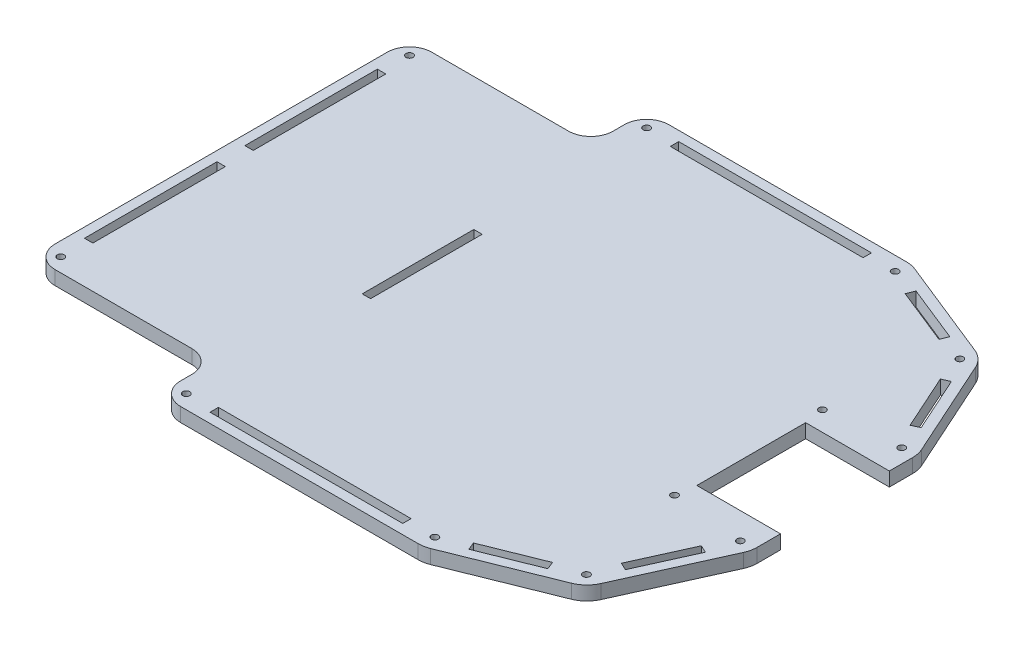
SolidWorks part; units mm, degrees
material "PVC rigido"
ref_plane "Piano frontale" through (0, 0, 0) normal (0, 0, 1) x (1, 0, 0)
ref_plane "Piano superiore" through (0, 0, 0) normal (0, 1, 0) x (1, 0, 0)
ref_plane "Piano destro" through (0, 0, 0) normal (1, 0, 0) x (0, 0, -1)
sketch "Schizzo1" plane through (0, 0, 0) normal (0, 1, 0) x (1, 0, 0)
  line L0 (65, 67.5) -> (65, 87.5)
  line L1 (0, 67.5) -> (65, 67.5)
  line L2 (0, 67.5) -> (0, -67.5)
  line L3 (0, -67.5) -> (65, -67.5)
  line L4 (65, 67.5) -> (65, -67.5) construction
  line L5 (65, 87.5) -> (160.0521, 87.5)
  line L6 (220, 30) -> (220, -30)
  line L7 (160.0521, -87.5) -> (65, -87.5)
  line L8 (65, -87.5) -> (65, -67.5)
  line L9 (220, 0) -> (65, 0) construction
  line L10 (220, 30) -> (201.5852, 70.8013)
  line L11 (201.5852, 70.8013) -> (160.0521, 87.5)
  line L12 (220, -30) -> (201.5852, -70.8013)
  line L13 (201.5852, -70.8013) -> (160.0521, -87.5)
  arc A0 (220, 30) -> (160.0521, 87.5) centre (160.0521, 27.5) ccw construction
  arc A1 (160.0521, -87.5) -> (220, -30) centre (160.0521, -27.5) ccw construction
  dimension "D5" = 60
  dimension "D6" = 60
  dimension "D1" = 135
  dimension "D2" = 65
  dimension "D3" = 155
  dimension "D4" = 20
extrude "Estrusione-Estrusione1" add sketch "Schizzo1" along normal blind 5
hole_wizard "Foro filettato M3x0.5-1" positions "Schizzo9" profile "Schizzo8" tap size "M3x0.5" standard "Ansi Metric"
sketch "Schizzo9" plane through (0, 5, 0) normal (0, 1, 0) x (1, 0, 0)
  line L102 (5, -62.5) -> (70, -62.5)
  line L103 (5, 62.5) -> (5, -62.5)
  line L104 (70, 62.5) -> (5, 62.5)
  line L105 (70, 82.5) -> (70, 62.5)
  line L106 (70, -62.5) -> (70, -82.5)
  line L107 (70, -82.5) -> (159.0846, -82.5)
  line L108 (159.0846, -82.5) -> (197.8549, -66.9121)
  line L109 (197.8549, -66.9121) -> (215, -28.9239)
  line L110 (215, -28.9239) -> (215, 28.9239)
  line L111 (215, 28.9239) -> (197.8549, 66.9121)
  line L112 (197.8549, 66.9121) -> (159.0846, 82.5)
  line L113 (159.0846, 82.5) -> (70, 82.5)
  line L114 (5, -62.5) -> (70, -62.5) construction
  line L115 (5, 62.5) -> (5, -62.5) construction
  line L116 (70, 62.5) -> (5, 62.5) construction
  line L117 (70, 82.5) -> (70, 62.5) construction
  line L118 (70, -62.5) -> (70, -82.5) construction
  line L119 (70, -82.5) -> (159.0846, -82.5) construction
  line L120 (159.0846, -82.5) -> (197.8549, -66.9121) construction
  line L121 (197.8549, -66.9121) -> (215, -28.9239) construction
  line L122 (215, -28.9239) -> (215, 28.9239) construction
  line L123 (215, 28.9239) -> (197.8549, 66.9121) construction
  line L124 (197.8549, 66.9121) -> (159.0846, 82.5) construction
  line L125 (159.0846, 82.5) -> (70, 82.5) construction
  point P0 (197.8549, 66.9121)
  point P2 (215, 28.9239)
  point P4 (215, -28.9239)
  point P6 (197.8549, -66.9121)
  point P8 (159.0846, -82.5)
  point P10 (159.0846, 82.5)
  point P12 (70, 82.5)
  point P14 (70, -82.5)
  point P16 (5, -62.5)
  point P18 (5, 62.5)
  dimension "D1" = 5
sketch "Schizzo8" plane through (197.8549, 5, -66.9121) normal (1, 0, 0) x (0, 0, 1)
  line L0 (0, 0) -> (0, 8.2511)
  line L1 (0, 8.2511) -> (1.25, 7.5)
  line L2 (1.25, 7.5) -> (1.25, 0)
  line L5 (1.25, 0) -> (0, 0)
  line L10 (0, 8.2511) -> (-1.25, 7.5) construction
  line L11 (0, -6.35) -> (0, 107.95) construction
  dimension "Tap Drill Dia." = 2.5
  dimension "Tap Drill Depth" = 7.5
  dimension "Drill Angle" = 118
cosmetic thread "Filettatura del foro1" parameters "D1"=5, "D2"=3
cosmetic thread "Filettatura del foro2" parameters "D1"=5, "D2"=3
cosmetic thread "Filettatura del foro3" parameters "D1"=5, "D2"=3
cosmetic thread "Filettatura del foro4" parameters "D1"=5, "D2"=3
cosmetic thread "Filettatura del foro5" parameters "D1"=5, "D2"=3
cosmetic thread "Filettatura del foro6" parameters "D1"=5, "D2"=3
cosmetic thread "Filettatura del foro7" parameters "D1"=5, "D2"=3
cosmetic thread "Filettatura del foro8" parameters "D1"=5, "D2"=3
cosmetic thread "Filettatura del foro9" parameters "D1"=5, "D2"=3
cosmetic thread "Filettatura del foro10" parameters "D1"=5, "D2"=3
sketch "Schizzo4" plane through (0, 5, 0) normal (0, 1, 0) x (1, 0, 0)
  line L0 (112.5261, -87.5) -> (112.5261, -84) construction
  line L1 (80, -84) -> (149.0846, -84)
  line L2 (80, -84) -> (80, -81)
  line L3 (80, -81) -> (149.0846, -81)
  line L4 (149.0846, -84) -> (149.0846, -81)
  line L5 (209.5191, 37.4216) -> (200.6014, 57.1804)
  line L6 (149.0846, -82.5) -> (159.0846, -82.5) construction
  line L7 (159.0846, -82.5) -> (168.3628, -78.7696) construction
  line L8 (168.3628, -78.7696) -> (188.5767, -70.6425) construction
  line L9 (80, 84) -> (149.0846, 84)
  line L10 (80, 84) -> (80, 81)
  line L11 (80, 81) -> (149.0846, 81)
  line L12 (149.0846, 84) -> (149.0846, 81)
  line L13 (65, -87.5) -> (160.0521, -87.5) construction
  line L14 (80, -82.5) -> (70, -82.5) construction
  line L15 (200.6014, 57.1804) -> (203.3358, 58.4145)
  line L16 (112.5261, 87.5) -> (112.5261, 84) construction
  line L17 (160.0521, 87.5) -> (65, 87.5) construction
  line L18 (80, 82.5) -> (70, 82.5) construction
  line L19 (203.3358, 58.4145) -> (212.2535, 38.6557)
  line L20 (188.5767, -70.6425) -> (197.8549, -66.9121) construction
  line L21 (197.8549, -66.9121) -> (201.9686, -57.7974) construction
  line L22 (201.9686, -57.7974) -> (210.8863, -38.0386) construction
  line L23 (210.8863, -38.0386) -> (215, -28.9239) construction
  line L24 (215, -28.9239) -> (215, -18.9239) construction
  line L25 (215, -18.9239) -> (215, 18.9239) construction
  line L26 (215, 18.9239) -> (215, 28.9239) construction
  line L27 (215, 28.9239) -> (210.8863, 38.0386) construction
  line L28 (210.8863, 38.0386) -> (201.9686, 57.7974) construction
  line L29 (201.9686, 57.7974) -> (197.8549, 66.9121) construction
  line L30 (197.8549, 66.9121) -> (188.5767, 70.6425) construction
  line L31 (188.5767, 70.6425) -> (168.3628, 78.7696) construction
  line L32 (168.3628, 78.7696) -> (159.0846, 82.5) construction
  line L33 (159.0846, 82.5) -> (149.0846, 82.5) construction
  line L34 (189.1362, 72.0342) -> (168.9223, 80.1614)
  line L35 (168.9223, 80.1614) -> (167.8032, 77.3779)
  line L36 (167.8032, 77.3779) -> (188.0171, 69.2507)
  line L37 (188.0171, 69.2507) -> (189.1362, 72.0342)
  line L38 (201.5852, 70.8013) -> (160.0521, 87.5) construction
  line L39 (212.2535, 38.6557) -> (209.5191, 37.4216)
  line L40 (167.8032, -77.3779) -> (188.0171, -69.2507)
  line L41 (188.0171, -69.2507) -> (189.1362, -72.0342)
  line L42 (189.1362, -72.0342) -> (168.9223, -80.1614)
  line L43 (168.9223, -80.1614) -> (167.8032, -77.3779)
  line L44 (200.6014, -57.1804) -> (209.5191, -37.4216)
  line L45 (209.5191, -37.4216) -> (212.2535, -38.6557)
  line L46 (212.2535, -38.6557) -> (203.3358, -58.4145)
  line L47 (203.3358, -58.4145) -> (200.6014, -57.1804)
  dimension "D1" = 10
  dimension "D2" = 3
extrude "Taglio-Estrusione2" cut sketch "Schizzo4" against normal blind 10
sketch "Schizzo7" plane through (0, 5, 0) normal (0, 1, 0) x (1, 0, 0)
  line L0 (5, -52.5) -> (5, -62.5) construction
  line L1 (3.5, 52.5) -> (6.5, 52.5)
  line L2 (3.5, 52.5) -> (3.5, 5)
  line L3 (3.5, 5) -> (6.5, 5)
  line L4 (6.5, 52.5) -> (6.5, 5)
  line L5 (6.5, -5) -> (3.5, -5)
  line L6 (6.5, -5) -> (6.5, -52.5)
  line L7 (6.5, -52.5) -> (3.5, -52.5)
  line L8 (3.5, -5) -> (3.5, -52.5)
  line L10 (5, 52.5) -> (5, 62.5) construction
  line L12 (5, -5) -> (5, 5) construction
  line L13 (5, 0) -> (0, 0) construction
  line L14 (0, 67.5) -> (0, -67.5) construction
  line L15 (80, -81) -> (80, -84) construction
  line L16 (80, -82.5) -> (70, -82.5) construction
  line L19 (3.5, -28.75) -> (0, -28.75) construction
  dimension "D2" = 10
extrude "Taglio-Estrusione5" cut sketch "Schizzo7" against normal blind 10
sketch "Schizzo12" plane through (0, 5, 0) normal (0, 1, 0) x (1, 0, 0)
  line L0 (114.5423, 81) -> (114.5423, -81) construction
  line L1 (70.5423, 20) -> (73.5423, 20)
  line L2 (70.5423, 20) -> (70.5423, -20)
  line L3 (70.5423, -20) -> (73.5423, -20)
  line L4 (73.5423, 20) -> (73.5423, -20)
  line L9 (80, 81) -> (149.0846, 81) construction
  line L10 (149.0846, -81) -> (80, -81) construction
  line L11 (73.5423, 0) -> (114.5423, 0) construction
  dimension "D1" = 40
  dimension "D2" = 3
  dimension "D3" = 44
extrude "Taglio-Estrusione8" cut sketch "Schizzo12" against normal through all
sketch "Schizzo2" plane through (0, 5, 0) normal (0, 1, 0) x (1, 0, 0)
  line L0 (220, 19.5) -> (190, 19.5)
  line L1 (220, -30) -> (220, 30) construction
  line L2 (190, 19.5) -> (190, -19.5)
  line L3 (190, -19.5) -> (220, -19.5)
  line L4 (190, 0) -> (220, 0) construction
  line L5 (220, -30) -> (220, -19.5) construction
  line L6 (220, 30) -> (220, 19.5) construction
  line L7 (220, -30) -> (220, 30) construction
  dimension "D1" = 30
  dimension "D2" = 39
extrude "Taglio-Estrusione1" cut sketch "Schizzo2" against normal through all and the other way through all
sketch "Schizzo11" plane through (0, 5, 0) normal (0, 1, 0) x (1, 0, 0)
  line L0 (220, -19.5) -> (190, -19.5) construction
  line L1 (213.5, -18.9239) -> (216.5, -18.9239)
  line L2 (213.5, -18.9239) -> (213.5, -19.5)
  line L3 (213.5, -19.5) -> (216.5, -19.5)
  line L4 (216.5, -18.9239) -> (216.5, -19.5)
  line L5 (190, 19.5) -> (220, 19.5) construction
  line L6 (213.5, 19.5) -> (216.5, 19.5)
  line L7 (213.5, 19.5) -> (213.5, 18.9239)
  line L8 (213.5, 18.9239) -> (216.5, 18.9239)
  line L9 (216.5, 19.5) -> (216.5, 18.9239)
  line L10 (212.2535, 38.6557) -> (209.5191, 37.4216) construction
  line L11 (209.5191, -37.4216) -> (212.2535, -38.6557) construction
extrude "Taglio-Estrusione7" [suppressed] cut sketch "Schizzo11" against normal blind 5
sketch "Schizzo10" [suppressed] plane through (0, 3, 0) normal (0, 1, 0) x (1, 0, 0)
  line L0 (212.2535, 38.6557) -> (209.5191, 37.4216) construction
  line L1 (213.5, -18.9239) -> (216.5, -18.9239)
  line L2 (213.5, -18.9239) -> (213.5, 18.9239)
  line L3 (213.5, 18.9239) -> (216.5, 18.9239)
  line L4 (216.5, -18.9239) -> (216.5, 18.9239)
extrude "Taglio-Estrusione6" [suppressed] cut sketch "Schizzo10" against normal through all
hole_wizard "Foro filettato M3x0.5-2" [suppressed] positions "Schizzo16" profile "Schizzo15" tap size "M3x0.5" standard "Ansi Metric"
sketch "Schizzo16" plane through (0, 3, 0) normal (0, 1, 0) x (1, 0, 0)
  line L0 (13, 54.5) -> (58, 54.5) construction
  line L1 (58, 54.5) -> (58, -54.5) construction
  line L2 (58, -54.5) -> (13, -54.5) construction
  line L3 (13, -54.5) -> (13, 54.5) construction
  line L5 (0, 0) -> (13, 0) construction
  line L6 (0, 67.5) -> (0, -67.5) construction
  circle A0 centre (13, -54.5) radius 1.25 construction
  circle A1 centre (58, -54.5) radius 1.25 construction
  point P0 (13, 54.5)
  point P2 (13, -54.5)
  point P4 (58, -54.5)
  point P6 (58, 54.5)
sketch "Schizzo15" plane through (13, 3, -54.5) normal (1, 0, 0) x (0, 0, 1)
  line L0 (0, 0) -> (0, 3)
  line L1 (0, 3) -> (1.25, 3)
  line L2 (1.25, 3) -> (1.25, 0)
  line L5 (1.25, 0) -> (0, 0)
  line L11 (0, -6.35) -> (0, 107.95) construction
  dimension "Thru Tap Drill Dia." = 2.5
  dimension "Thru Tap Drill Depth" = 3
cosmetic thread "Filettatura del foro11" [suppressed] parameters "D2"=3
cosmetic thread "Filettatura del foro12" [suppressed] parameters "D2"=3
cosmetic thread "Filettatura del foro13" [suppressed] parameters "D2"=3
cosmetic thread "Filettatura del foro14" [suppressed] parameters "D2"=3
sketch "Schizzo17" [suppressed] plane through (0, 3, 0) normal (0, 1, 0) x (1, 0, 0)
  line L0 (58, -54.5) -> (48, -54.5) construction
  line L1 (48, -54.5) -> (23, -54.5) construction
  line L2 (23, -54.5) -> (13, -54.5) construction
  line L3 (13, -54.5) -> (13, -44.5) construction
  line L4 (13, -44.5) -> (13, 44.5) construction
  line L5 (13, 44.5) -> (13, 54.5) construction
  line L6 (13, 54.5) -> (23, 54.5) construction
  line L7 (23, 54.5) -> (48, 54.5) construction
  line L8 (48, 54.5) -> (58, 54.5) construction
  line L9 (48, -56) -> (48, -53) construction
  line L10 (23, -53) -> (48, -53)
  line L11 (23, -53) -> (23, -56)
  line L12 (23, -56) -> (48, -56)
  line L13 (48, -53) -> (48, -56)
  line L14 (14.5, -44.5) -> (11.5, -44.5)
  line L15 (14.5, -44.5) -> (14.5, -24.5)
  line L16 (14.5, 44.5) -> (11.5, 44.5)
  line L17 (11.5, -44.5) -> (11.5, -24.5)
  line L18 (23, 56) -> (48, 56)
  line L19 (23, 56) -> (23, 53)
  line L20 (23, 53) -> (48, 53)
  line L21 (48, 56) -> (48, 53)
  line L22 (11.5, 24.5) -> (14.5, 24.5)
  line L23 (11.5, 12.5) -> (14.5, 12.5)
  line L24 (11.5, 24.5) -> (11.5, 44.5)
  line L25 (14.5, 24.5) -> (14.5, 44.5)
  line L26 (11.5, -24.5) -> (14.5, -24.5)
  line L27 (11.5, -12.5) -> (14.5, -12.5)
  line L28 (11.5, -12.5) -> (11.5, 12.5)
  line L29 (14.5, -12.5) -> (14.5, 12.5)
  line L30 (13, 0) -> (11.5, 0) construction
  dimension "D2" = 25
  dimension "D1" = 3
  dimension "D3" = 20
extrude "Taglio-Estrusione9" [suppressed] cut sketch "Schizzo17" against normal blind 10
sketch "Schizzo18" [suppressed] plane through (0, 3, 0) normal (0, 1, 0) x (1, 0, 0)
  line L0 (113, -72.5) -> (113, 0) construction
  line L1 (78, 74.5) -> (148, 74.5)
  line L2 (78, 74.5) -> (78, 72.5)
  line L3 (78, 72.5) -> (148, 72.5)
  line L4 (148, 74.5) -> (148, 72.5)
  line L5 (78, -72.5) -> (148, -72.5)
  line L6 (78, -72.5) -> (78, -74.5)
  line L7 (78, -74.5) -> (148, -74.5)
  line L8 (148, -72.5) -> (148, -74.5)
  line L9 (113, 0) -> (113, 72.5) construction
  line L10 (0, 0) -> (113, 0) construction
  line L11 (148, -72.5) -> (78, -72.5) construction
  line L12 (78, -72.5) -> (78, -74.5) construction
  line L13 (78, -74.5) -> (148, -74.5) construction
extrude "Taglio-Estrusione10" [suppressed] cut sketch "Schizzo18" against normal blind 10
hole_wizard "Foro filettato M3x0.5-3" [suppressed] positions "Schizzo20" profile "Schizzo19" tap size "M3x0.5" standard "Ansi Metric"
sketch "Schizzo20" plane through (0, 3, 0) normal (0, 1, 0) x (1, 0, 0)
  line L0 (207, 26.4239) -> (207, 0) construction
  line L1 (207, 0) -> (207, -26.4239) construction
  line L5 (220, 0) -> (207, 0) construction
  line L6 (220, -30) -> (220, 30) construction
  point P0 (207, 26.4239)
  point P2 (207, -26.4239)
sketch "Schizzo19" plane through (207, 3, -26.4239) normal (1, 0, 0) x (0, 0, 1)
  line L0 (0, 0) -> (0, 3)
  line L1 (0, 3) -> (1.25, 3)
  line L2 (1.25, 3) -> (1.25, 0)
  line L5 (1.25, 0) -> (0, 0)
  line L11 (0, -6.35) -> (0, 107.95) construction
  dimension "Thru Tap Drill Dia." = 2.5
  dimension "Thru Tap Drill Depth" = 3
cosmetic thread "Filettatura del foro15" [suppressed] parameters "D2"=3
cosmetic thread "Filettatura del foro16" [suppressed] parameters "D2"=3
hole_wizard "Foro filettato M3x0.5-4" positions "Schizzo22" profile "Schizzo21" tap size "M3x0.5" standard "Ansi Metric" end condition through all
sketch "Schizzo22" plane through (0, 5, 0) normal (0, 1, 0) x (1, 0, 0)
  line L0 (189, 26.5) -> (189, -26.5) construction
  point P0 (189, 26.5)
  point P2 (189, -26.5)
sketch "Schizzo21" plane through (189, 5, -26.5) normal (1, 0, 0) x (0, 0, 1)
  line L0 (0, 0) -> (0, 5)
  line L1 (0, 5) -> (1.25, 5)
  line L2 (1.25, 5) -> (1.25, 0)
  line L5 (1.25, 0) -> (0, 0)
  line L11 (0, -6.35) -> (0, 107.95) construction
  dimension "Thru Tap Drill Dia." = 2.5
  dimension "Thru Tap Drill Depth" = 5
cosmetic thread "Filettatura del foro17" parameters "D2"=3
cosmetic thread "Filettatura del foro18" parameters "D2"=3
fillet "Raccordo1" radius 8 6 edges at (0, 2.5, 67.5) (0, 2.5, -67.5) (65, 2.5, -87.5) (65, 2.5, 87.5) (65, 2.5, 67.5) (65, 2.5, -67.5)
fillet "Raccordo2" radius 10 6 edges at (160.0521, 2.5, -87.5) (201.5852, 2.5, -70.8013) (220, 2.5, -30) (220, 2.5, 30) (201.5852, 2.5, 70.8013) (160.0521, 2.5, 87.5)
